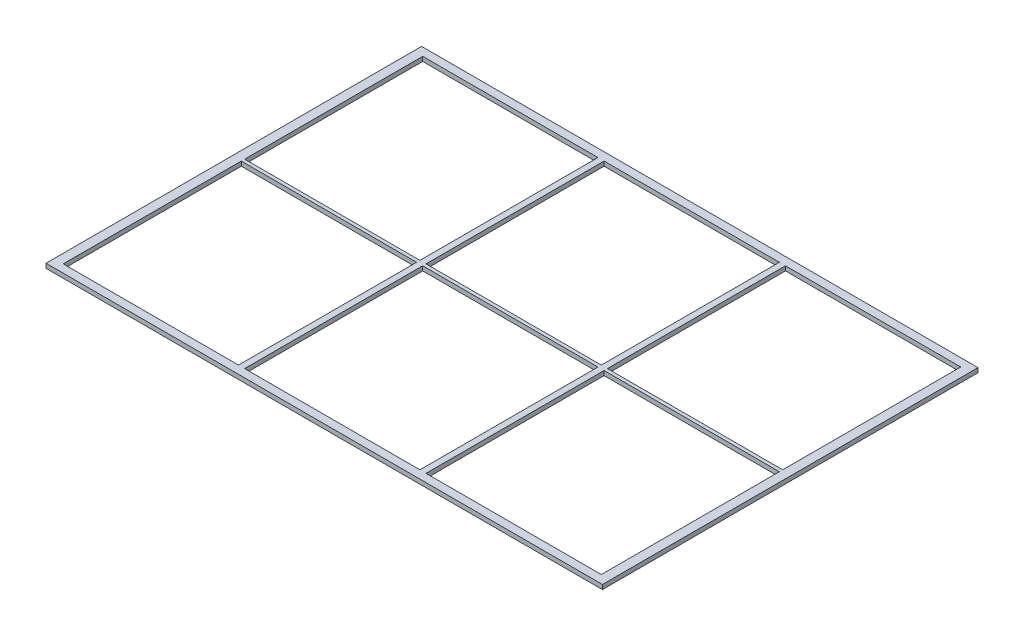
SolidWorks part; units mm, degrees
ref_plane "Front Plane" through (0, 0, 0) normal (0, 0, 1) x (1, 0, 0)
ref_plane "Top Plane" through (0, 0, 0) normal (0, 1, 0) x (1, 0, 0)
ref_plane "Right Plane" through (0, 0, 0) normal (1, 0, 0) x (0, 0, -1)
sketch "Sketch1" plane through (0, 0, 0) normal (0, 1, 0) x (1, 0, 0)
  line L1 (100, -67.5) -> (-100, -67.5)
  line L2 (100, -67.5) -> (100, 67.5)
  line L3 (100, 67.5) -> (-100, 67.5)
  line L4 (-100, -67.5) -> (-100, 67.5)
  line L5 (100, -67.5) -> (-100, 67.5) construction
  line L6 (100, 67.5) -> (-100, -67.5) construction
  point P0 (0, 0)
  dimension "D1" = 200
  dimension "D2" = 135
extrude "Boss-Extrude1" add sketch "Sketch1" along normal blind 1.6
sketch "Sketch2" plane through (0, 1.6, 0) normal (0, 1, 0) x (1, 0, 0)
  line L0 (100, 67.5) -> (-100, 67.5) construction
  line L1 (-96.7, 64.6) -> (-33.7, 64.6)
  line L2 (-96.7, 64.6) -> (-96.7, 0.6)
  line L3 (-96.7, 0.6) -> (-33.7, 0.6)
  line L4 (-33.7, 64.6) -> (-33.7, 0.6)
  line L5 (-100, 67.5) -> (-100, -67.5) construction
  dimension "D1" = 63
  dimension "D2" = 64
  dimension "D3" = 2.9
  dimension "D4" = 3.3
extrude "Cut-Extrude1" cut sketch "Sketch2" against normal blind 1.6
pattern_linear "LPattern1" count 3 spacing 65.2 along (1, 0, 0) count 2 spacing 65.2 along (0, 0, 1) of "Cut-Extrude1"
